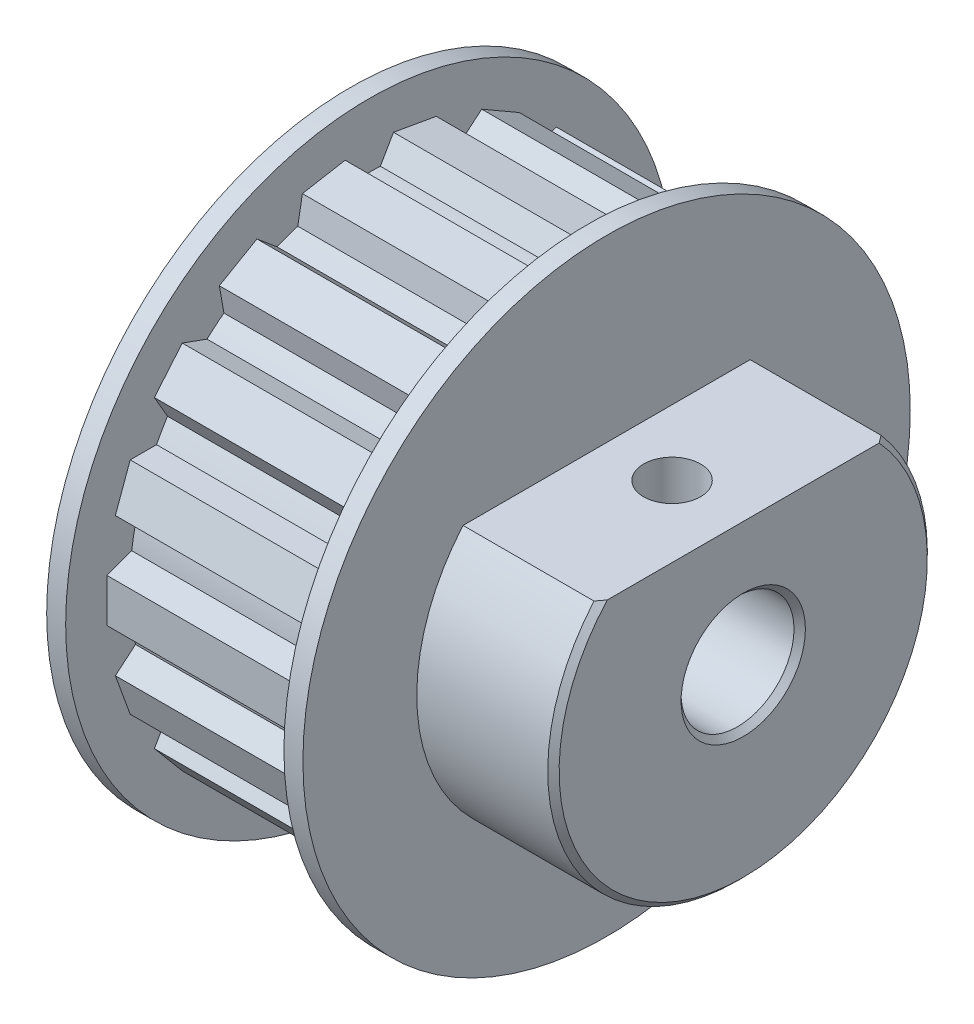
SolidWorks part; units mm, degrees
ref_plane "Front Plane" through (0, 0, 0) normal (0, 0, 1) x (1, 0, 0)
ref_plane "Top Plane" through (0, 0, 0) normal (0, 1, 0) x (1, 0, 0)
ref_plane "Right Plane" through (0, 0, 0) normal (1, 0, 0) x (0, 0, -1)
sketch "Sketch1" plane through (0, 0, 0) normal (0, 0, 1) x (1, 0, 0)
  line L0 (0, 16) -> (0, 0)
  line L1 (0, 0) -> (13.5, 0)
  line L2 (13.5, 0) -> (13.5, 16)
  line L3 (13.5, 16) -> (12.5, 16)
  line L4 (12.5, 16) -> (12.5, 13.9)
  line L5 (12.5, 13.9) -> (12.5, 12.6239)
  line L6 (12.5, 12.6239) -> (1, 12.6239)
  line L7 (1, 12.6239) -> (1, 13.9)
  line L8 (1, 13.9) -> (1, 16)
  line L9 (1, 16) -> (0, 16)
  line L10 (0, 0) -> (13.5, 0) construction
  point P10 (0, 0)
  dimension "D1" = 16
  dimension "D2" = 12.6239
  dimension "D3" = 1.2761
  dimension "D4" = 1.2761
  dimension "D5" = 16
  dimension "D6" = 11.5
  dimension "D7" = 1
  dimension "D8" = 1
revolve "Revolve1" add sketch "Sketch1" angle 360 about L10
sketch "Sketch2" plane through (13.5, 0, 0) normal (1, 0, 0) x (0, 0, -1)
  circle A0 centre (0, 0) radius 10
extrude "Boss-Extrude1" add sketch "Sketch2" along normal blind 7.2
hole_wizard "Ø6.0 (6) Diameter Hole1" positions "Sketch4" profile "Sketch3" hole size "Ø6.0" standard "ANSI Metric"
sketch "Sketch4" plane through (20.7, 0, 0) normal (1, 0, 0) x (0, 0, -1)
  point P0 (0, 0)
sketch "Sketch3" plane through (20.7, 0, 0) normal (0, 1, 0) x (0, 0, -1)
  line L0 (0, 0) -> (0, 20.7)
  line L1 (0, 20.7) -> (2.975, 20.7)
  line L2 (2.975, 20.7) -> (2.975, 0)
  line L5 (2.975, 0) -> (0, 0)
  line L11 (0, -6.35) -> (0, 107.95) construction
  dimension "Thru Hole Dia." = 5.95
  dimension "Thru Hole Depth" = 20.7
ref_plane "Plane1" through (0, 0, 0) normal (0, -1, 0) x (1, 0, 0)
sketch "Sketch5" plane through (0, 0, 0) normal (0, -1, 0) x (1, 0, 0)
  line L0 (12.65, 13.8239) -> (1.15, 13.8239)
rib "Rib1" sketch "Sketch5" sketch "Sketch5" thickness 2.2868 extrusion direction parallel to sketch draft on yes draft angle 20 parameters "D1"=2.2868, "D3"=20
sketch "Sketch6" plane through (0, 0, 0) normal (0, 1, 0) x (1, 0, 0)
  line L0 (12.65, 13.8239) -> (1.15, 13.8239)
rib "Rib2" sketch "Sketch6" sketch "Sketch6" thickness 2.2868 extrusion direction parallel to sketch draft on yes draft angle 20 parameters "D1"=2.2868, "D3"=20
ref_plane "Plane2" through (0, 0, 0) normal (0, 0.5, -0.866) x (-1, 0, 0)
sketch "Sketch7" plane through (0, 0, 0) normal (0, 0.5, -0.866) x (-1, 0, 0)
  line L0 (-12.65, -13.8239) -> (-1.15, -13.8239)
rib "Rib3" sketch "Sketch7" sketch "Sketch7" thickness 2.2868 extrusion direction parallel to sketch draft on yes draft angle 20 parameters "D1"=2.2868, "D3"=20
ref_plane "Plane3" through (0, 0, 0) normal (0, 0.9397, 0.342) x (-1, 0, 0)
sketch "Sketch8" plane through (0, 0, 0) normal (0, 0.9397, 0.342) x (-1, 0, 0)
  line L0 (-12.65, -13.8239) -> (-1.15, -13.8239)
rib "Rib4" sketch "Sketch8" sketch "Sketch8" thickness 2.2868 extrusion direction parallel to sketch draft on yes draft angle 20 parameters "D1"=2.2868, "D3"=20
ref_plane "Plane4" through (0, 0, 0) normal (0, -0.9397, -0.342) x (1, 0, 0)
sketch "Sketch9" plane through (0, 0, 0) normal (0, -0.9397, -0.342) x (1, 0, 0)
  line L0 (12.65, 13.8239) -> (1.15, 13.8239)
rib "Rib5" sketch "Sketch9" sketch "Sketch9" thickness 2.2868 extrusion direction parallel to sketch draft on yes draft angle 20 parameters "D1"=2.2868, "D3"=20
ref_plane "Plane5" through (0, 0, 0) normal (0, -0.1736, -0.9848) x (1, 0, 0)
sketch "Sketch10" plane through (0, 0, 0) normal (0, -0.1736, -0.9848) x (1, 0, 0)
  line L0 (12.65, 13.8239) -> (1.15, 13.8239)
rib "Rib6" sketch "Sketch10" sketch "Sketch10" thickness 2.2868 extrusion direction parallel to sketch draft on yes draft angle 20 parameters "D1"=2.2868, "D3"=20
ref_plane "Plane6" through (0, 0, 0) normal (0, -0.1736, 0.9848) x (1, 0, 0)
sketch "Sketch11" plane through (0, 0, 0) normal (0, -0.1736, 0.9848) x (1, 0, 0)
  line L0 (12.65, 13.8239) -> (1.15, 13.8239)
rib "Rib7" sketch "Sketch11" sketch "Sketch11" thickness 2.2868 extrusion direction parallel to sketch draft on yes draft angle 20 parameters "D1"=2.2868, "D3"=20
ref_plane "Plane7" through (0, 0, 0) normal (0, 0.1736, -0.9848) x (-1, 0, 0)
sketch "Sketch12" plane through (0, 0, 0) normal (0, 0.1736, -0.9848) x (-1, 0, 0)
  line L0 (-12.65, -13.8239) -> (-1.15, -13.8239)
rib "Rib8" sketch "Sketch12" sketch "Sketch12" thickness 2.2868 extrusion direction parallel to sketch draft on yes draft angle 20 parameters "D1"=2.2868, "D3"=20
ref_plane "Plane8" through (0, 0, 0) normal (0, 0.5, 0.866) x (-1, 0, 0)
sketch "Sketch13" plane through (0, 0, 0) normal (0, 0.5, 0.866) x (-1, 0, 0)
  line L0 (-12.65, -13.8239) -> (-1.15, -13.8239)
rib "Rib9" sketch "Sketch13" sketch "Sketch13" thickness 2.2868 extrusion direction parallel to sketch draft on yes draft angle 20 parameters "D1"=2.2868, "D3"=20
ref_plane "Plane9" through (0, 0, 0) normal (0, 0.9397, -0.342) x (-1, 0, 0)
sketch "Sketch14" plane through (0, 0, 0) normal (0, 0.9397, -0.342) x (-1, 0, 0)
  line L0 (-12.65, -13.8239) -> (-1.15, -13.8239)
rib "Rib10" sketch "Sketch14" sketch "Sketch14" thickness 2.2868 extrusion direction parallel to sketch draft on yes draft angle 20 parameters "D1"=2.2868, "D3"=20
ref_plane "Plane10" through (0, 0, 0) normal (0, 0.1736, 0.9848) x (-1, 0, 0)
sketch "Sketch15" plane through (0, 0, 0) normal (0, 0.1736, 0.9848) x (-1, 0, 0)
  line L0 (-12.65, -13.8239) -> (-1.15, -13.8239)
rib "Rib11" sketch "Sketch15" sketch "Sketch15" thickness 2.2868 extrusion direction parallel to sketch draft on yes draft angle 20 parameters "D1"=2.2868, "D3"=20
ref_plane "Plane11" through (0, 0, 0) normal (0, -0.766, -0.6428) x (1, 0, 0)
sketch "Sketch16" plane through (0, 0, 0) normal (0, -0.766, -0.6428) x (1, 0, 0)
  line L0 (12.65, 13.8239) -> (1.15, 13.8239)
rib "Rib12" sketch "Sketch16" sketch "Sketch16" thickness 2.2868 extrusion direction parallel to sketch draft on yes draft angle 20 parameters "D1"=2.2868, "D3"=20
ref_plane "Plane12" through (0, 0, 0) normal (0, -0.9397, 0.342) x (1, 0, 0)
sketch "Sketch17" plane through (0, 0, 0) normal (0, -0.9397, 0.342) x (1, 0, 0)
  line L0 (12.65, 13.8239) -> (1.15, 13.8239)
rib "Rib13" sketch "Sketch17" sketch "Sketch17" thickness 2.2868 extrusion direction parallel to sketch draft on yes draft angle 20 parameters "D1"=2.2868, "D3"=20
ref_plane "Plane13" through (0, 0, 0) normal (0, -0.766, 0.6428) x (1, 0, 0)
sketch "Sketch18" plane through (0, 0, 0) normal (0, -0.766, 0.6428) x (1, 0, 0)
  line L0 (12.65, 13.8239) -> (1.15, 13.8239)
rib "Rib14" sketch "Sketch18" sketch "Sketch18" thickness 2.2868 extrusion direction parallel to sketch draft on yes draft angle 20 parameters "D1"=2.2868, "D3"=20
ref_plane "Plane14" through (0, 0, 0) normal (0, -0.5, -0.866) x (1, 0, 0)
sketch "Sketch19" plane through (0, 0, 0) normal (0, -0.5, -0.866) x (1, 0, 0)
  line L0 (12.65, 13.8239) -> (1.15, 13.8239)
rib "Rib15" sketch "Sketch19" sketch "Sketch19" thickness 2.2868 extrusion direction parallel to sketch draft on yes draft angle 20 parameters "D1"=2.2868, "D3"=20
ref_plane "Plane15" through (0, 0, 0) normal (0, -0.5, 0.866) x (1, 0, 0)
sketch "Sketch20" plane through (0, 0, 0) normal (0, -0.5, 0.866) x (1, 0, 0)
  line L0 (12.65, 13.8239) -> (1.15, 13.8239)
rib "Rib16" sketch "Sketch20" sketch "Sketch20" thickness 2.2868 extrusion direction parallel to sketch draft on yes draft angle 20 parameters "D1"=2.2868, "D3"=20
ref_plane "Plane16" through (0, 0, 0) normal (0, 0.766, 0.6428) x (-1, 0, 0)
sketch "Sketch21" plane through (0, 0, 0) normal (0, 0.766, 0.6428) x (-1, 0, 0)
  line L0 (-12.65, -13.8239) -> (-1.15, -13.8239)
rib "Rib17" sketch "Sketch21" sketch "Sketch21" thickness 2.2868 extrusion direction parallel to sketch draft on yes draft angle 20 parameters "D1"=2.2868, "D3"=20
ref_plane "Plane17" through (0, 0, 0) normal (0, 0.766, -0.6428) x (-1, 0, 0)
sketch "Sketch22" plane through (0, 0, 0) normal (0, 0.766, -0.6428) x (-1, 0, 0)
  line L0 (-12.65, -13.8239) -> (-1.15, -13.8239)
rib "Rib18" sketch "Sketch22" sketch "Sketch22" thickness 2.2868 extrusion direction parallel to sketch draft on yes draft angle 20 parameters "D1"=2.2868, "D3"=20
chamfer "Chamfer1" distance 0.3 angle 45 3 edges at (20.7, 0, -10) (0, 0, -2.975) (20.7, 0, -2.975)
sketch "Sketch23" plane through (20.7, 0, 0) normal (1, 0, 0) x (0, 0, -1)
  line L0 (-7.5622, 6.5432) -> (7.5622, 6.5432)
  line L1 (-7.5622, 6.5432) -> (-7.5622, 11.9214)
  line L2 (7.5622, 6.5432) -> (7.5622, 11.9214)
  line L3 (-7.5622, 11.9214) -> (7.5622, 11.9214)
  circle A1 centre (0, 0) radius 10 construction
  circle A2 centre (0, 0) radius 10 construction
  point P0 (7.5622, 6.5432)
  point P6 (0, 0)
  point P7 (-7.5825, 6.5196)
extrude "Cut-Extrude2" cut sketch "Sketch23" against normal blind 7.2
sketch "Sketch24" plane through (0, 6.5432, 0) normal (0, 1, 0) x (1, 0, 0)
  line L0 (20.7, 0) -> (13.5, 0) construction
  line L1 (20.7, -7.1608) -> (20.7, 7.1608) construction
  line L2 (13.5, -7.5622) -> (13.5, 7.5622) construction
  line L3 (16.95, 7.5622) -> (16.95, -7.5622) construction
  line L4 (13.5, 7.5622) -> (20.4, 7.5622) construction
  line L5 (13.5, -7.5622) -> (20.4, -7.5622) construction
  circle A0 centre (16.95, 0) radius 1.5
  dimension "D1" = 3
extrude "Cut-Extrude3" cut sketch "Sketch24" against normal blind 7.2
